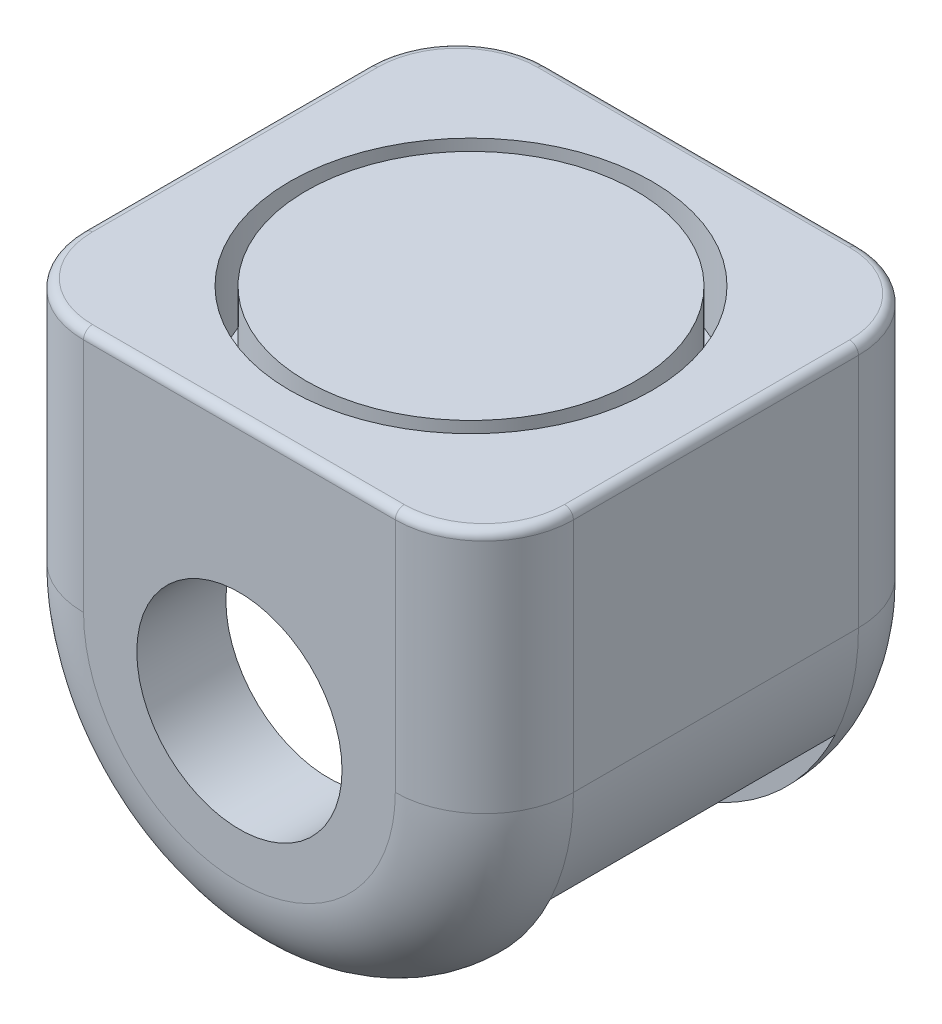
SolidWorks part; units mm, degrees
other "Markup1"
sketch "Sketch6" plane through (32.5, 40, -30) normal (0.2507, 0.8626, -0.4394) x (-0.8645, -0.0047, -0.5026)
ref_plane "Front Plane" through (0, 0, 0) normal (0, 0, 1) x (1, 0, 0)
ref_plane "Top Plane" through (0, 0, 0) normal (0, 1, 0) x (1, 0, 0)
ref_plane "Right Plane" through (0, 0, 0) normal (1, 0, 0) x (0, 0, -1)
sketch "Sketch1" plane through (0, 0, 0) normal (0, 1, 0) x (1, 0, 0)
  circle A0 centre (0, 0) radius 20.325
  dimension "D1" = 40.65
sketch "Sketch2" plane through (0, 0, 0) normal (0, 0, 1) x (1, 0, 0)
  line L0 (-27.5, -27.5) -> (-27.5, 0)
  line L1 (-27.5, 0) -> (27.5, 0)
  line L2 (27.5, 0) -> (27.5, -27.5)
  arc A0 (-27.5, -27.5) -> (27.5, -27.5) centre (0, -27.5) ccw
  dimension "D1" = 55
extrude "Boss-Extrude1" add sketch "Sketch2" along normal mid plane 52 separate body
sketch "Sketch3" plane through (0, 0, 0) normal (0, 1, 0) x (1, 0, 0)
  line L0 (-18.5, 0) -> (-20.325, 0) construction
  circle A0 centre (0, 0) radius 20.325
  circle A1 centre (0, 0) radius 18.5
  point P21 (0, 0)
  dimension "D3" = 40.65
  dimension "D4" = 37
extrude "Cut-Extrude1" cut sketch "Sketch3" against normal blind 10
sketch "Sketch5" [suppressed] plane through (0, 0, 0) normal (0, 0, 1) x (1, 0, 0)
  line L0 (-0.0105, 0) -> (-27.325, 0)
  line L1 (-27.325, 40) -> (-27.325, 0) construction
  line L2 (-27.325, 0) -> (-27.325, -9.0775)
  arc A1 (-0.0105, 0) -> (-27.325, -9.0775) centre (-0.0105, -45.6339) ccw
fillet "Fillet1" radius 10 6 edges at (27.5, -13.75, -26) (0, -55, -26) (27.5, -13.75, 26) (0, -55, 26) (-27.5, -13.75, -26) (-27.5, -13.75, 26)
fillet "Fillet5" radius 1 8 edges at (24.5711, 0, 23.0711) (0, 0, 26) (0, 0, -26) (24.5711, 0, -23.0711) (-24.5711, 0, 23.0711) (-24.5711, 0, -23.0711) (27.5, 0, 0) (-27.5, 0, 0)
sketch "Sketch7" plane through (0, 0, 0) normal (0, 0, 1) x (1, 0, 0)
  line L0 (-0.0113, -11.8764) -> (-25.0113, -11.8764)
  line L1 (-25.0113, -11.8764) -> (-25.0113, -36.8764)
  line L6 (24.9887, -36.8764) -> (24.9887, -11.8764)
  line L7 (24.9887, -11.8764) -> (-0.0113, -11.8764)
  arc A0 (-25.0113, -36.8764) -> (24.9887, -36.8764) centre (-0.0113, -36.8764) ccw
  dimension "D1" = 50
extrude "Cut-Extrude2" cut sketch "Sketch7" against normal mid plane 32
sketch "Sketch10" plane through (0, 0, 26) normal (0, 0, 1) x (1, 0, 0)
  circle A0 centre (0, -28.3193) radius 11.52
  dimension "D1" = 23.04
extrude "Cut-Extrude4" cut sketch "Sketch10" against normal blind 75
